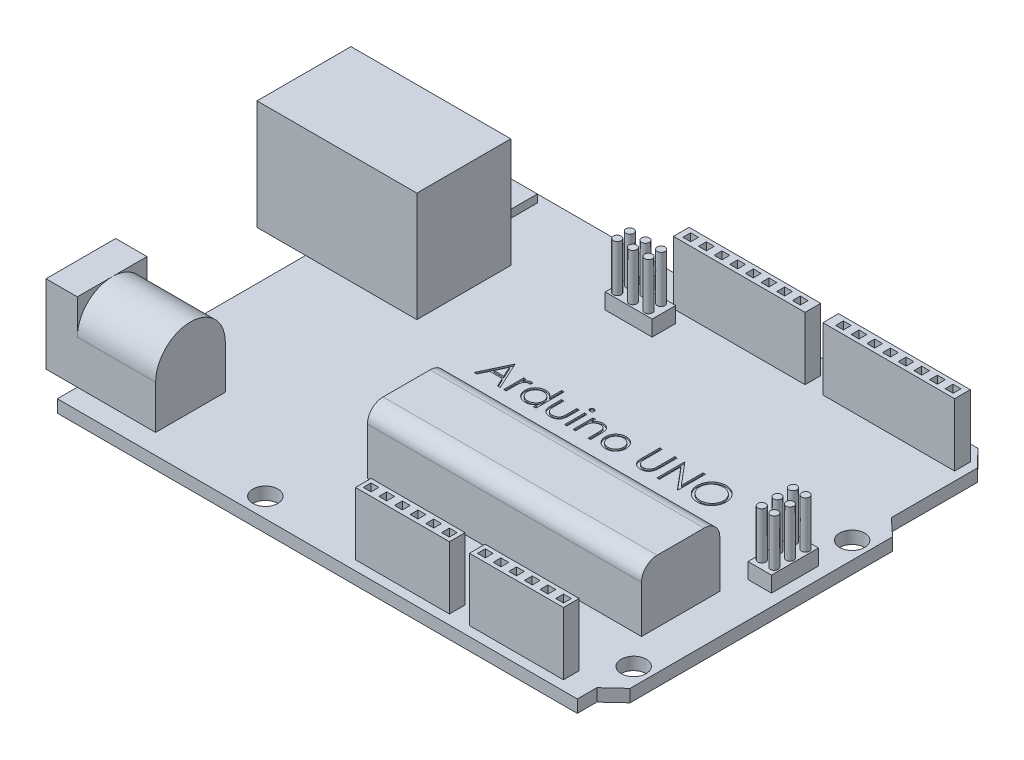
SolidWorks part; units mm, degrees
ref_plane "Plan de face" through (0, 0, 0) normal (0, 0, 1) x (1, 0, 0)
ref_plane "Plan de dessus" through (0, 0, 0) normal (0, 1, 0) x (1, 0, 0)
ref_plane "Plan de droite" through (0, 0, 0) normal (1, 0, 0) x (0, 0, -1)
sketch "Esquisse1" plane through (0, 0, 0) normal (0, 1, 0) x (1, 0, 0)
  line L0 (32.1, -43.7952) -> (32.1, 35.5676) construction
  line L1 (29.9738, 26.8233) -> (-34.3, 26.8233)
  line L2 (34.3, 11.5857) -> (34.3, -26.8233)
  line L3 (32.1, -26.4767) -> (-34.3, -26.4767)
  line L4 (-34.3, 26.8233) -> (-34.3, -26.4767)
  line L5 (34.2991, 26.4761) -> (-34.3, -26.4767) construction
  line L6 (34.3, -26.8233) -> (-34.3, 26.8233) construction
  line L7 (-10.2382, -23.9767) -> (42.0419, -23.9767) construction
  line L8 (32.1, -26.4767) -> (32.1, -23.9767)
  line L9 (32.1, -23.9767) -> (34.3, -21.9371)
  line L10 (34.3, -21.9371) -> (34.3, 11.5857)
  line L11 (34.3, 11.5857) -> (32.1, 13.6253)
  line L12 (32.1, 13.6253) -> (32.1, 24.6021)
  line L13 (32.1, 24.6021) -> (29.9738, 26.8233)
  circle A0 centre (32.1, 8.6233) radius 1.6
  circle A1 centre (32.1, -19.2767) radius 1.6
  circle A2 centre (-10.2382, -23.9767) radius 1.6
  circle A3 centre (-9.1382, 23.8233) radius 1.6
  point P0 (0, 0)
  dimension "D3" = 3.2
  dimension "D4" = 3.2
  dimension "D5" = 3.2
  dimension "D6" = 3.2
  dimension "D1" = 53.3
  dimension "D2" = 68.6
  dimension "D7" = 1.1
  dimension "D8" = 4.7
  dimension "D9" = 15.2
  dimension "D10" = 27.9
  dimension "D11" = 2.2
  dimension "D12" = 2.2
  dimension "D13" = 2.5
  dimension "D14" = 3
  dimension "D15" = 3
  dimension "D16" = 3
  dimension "D17" = 4.7
  dimension "D18" = 15.2
  dimension "D19" = 41.2382
  dimension "D20" = 42.3382
extrude "PLAQUE" add sketch "Esquisse1" along normal blind 1.6 contours L12 L13 L1 L4 L3 L8 L9 L2 L11 A3 A2 A1 A0
sketch "Esquisse3" plane through (0, 1.6, 0) normal (0, 1, 0) x (1, 0, 0)
  line L0 (-13.9042, -26.4767) -> (-13.9042, 26.8233) construction
  line L1 (32.1, -26.4767) -> (-34.3, -26.4767) construction
  line L2 (29.9738, 26.8233) -> (-34.3, 26.8233) construction
  line L4 (-34.3, 26.8233) -> (-34.3, -26.4767) construction
  line L9 (-20.0945, 17.2233) -> (-40.5, 17.2233)
  line L10 (-20.0945, 17.2233) -> (-20.0945, 5.2233)
  line L11 (-20.0945, 5.2233) -> (-40.5, 5.2233)
  line L12 (-40.5, 17.2233) -> (-40.5, 5.2233)
  line L13 (-20.0945, 17.2233) -> (-40.5, 5.2233) construction
  line L14 (-20.0945, 5.2233) -> (-40.5, 17.2233) construction
  point P10 (-30.2972, 11.2233)
  dimension "D3" = 14.2055
  dimension "D4" = 6.2
  dimension "D6" = 12
  dimension "D7" = 9.6
extrude "USB" add sketch "Esquisse3" along normal blind 14
sketch "Esquisse6" plane through (0, 1.6, 0) normal (0, 1, 0) x (1, 0, 0)
  text T0 "Arduino UNO"
extrude "Arduino UNO" cut sketch "Esquisse6" against normal blind 0.2
sketch "Esquisse7" plane through (0, 1.6, 0) normal (0, 1, 0) x (1, 0, 0)
  line L0 (-10.2382, -23.9767) -> (36.4939, -23.9767) construction
  line L1 (1.4601, -24.2464) -> (39.7542, -24.2464) construction
  line L2 (15.823, -25.4268) -> (15.823, -21.9072) construction
  line L3 (29.1021, -25.2464) -> (17.1021, -25.2464)
  line L4 (29.1021, -25.2464) -> (29.1021, -23.2464)
  line L5 (29.1021, -23.2464) -> (17.1021, -23.2464)
  line L6 (17.1021, -25.2464) -> (17.1021, -23.2464)
  line L7 (29.1021, -25.2464) -> (17.1021, -23.2464) construction
  line L8 (29.1021, -23.2464) -> (17.1021, -25.2464) construction
  line L9 (2.5439, -25.2464) -> (2.5439, -23.2464)
  line L10 (2.5439, -25.2464) -> (14.5439, -25.2464)
  line L11 (14.5439, -25.2464) -> (14.5439, -23.2464)
  line L12 (2.5439, -23.2464) -> (14.5439, -23.2464)
  line L13 (26.6165, -24.7464) -> (25.6165, -24.7464)
  line L14 (28.6165, -23.7464) -> (27.6165, -23.7464)
  line L15 (28.6165, -23.7464) -> (28.6165, -24.7464)
  line L16 (28.6165, -24.7464) -> (27.6165, -24.7464)
  line L17 (27.6165, -23.7464) -> (27.6165, -24.7464)
  line L18 (28.6165, -23.7464) -> (27.6165, -24.7464) construction
  line L19 (28.6165, -24.7464) -> (27.6165, -23.7464) construction
  line L20 (25.6165, -23.7464) -> (25.6165, -24.7464)
  line L21 (26.6165, -23.7464) -> (25.6165, -23.7464)
  line L22 (26.6165, -23.7464) -> (26.6165, -24.7464)
  line L23 (24.6165, -24.7464) -> (23.6165, -24.7464)
  line L24 (23.6165, -23.7464) -> (23.6165, -24.7464)
  line L25 (24.6165, -23.7464) -> (23.6165, -23.7464)
  line L26 (24.6165, -23.7464) -> (24.6165, -24.7464)
  line L27 (22.6165, -24.7464) -> (21.6165, -24.7464)
  line L28 (21.6165, -23.7464) -> (21.6165, -24.7464)
  line L29 (22.6165, -23.7464) -> (21.6165, -23.7464)
  line L30 (22.6165, -23.7464) -> (22.6165, -24.7464)
  line L31 (20.6165, -24.7464) -> (19.6165, -24.7464)
  line L32 (19.6165, -23.7464) -> (19.6165, -24.7464)
  line L33 (20.6165, -23.7464) -> (19.6165, -23.7464)
  line L34 (20.6165, -23.7464) -> (20.6165, -24.7464)
  line L35 (18.6165, -24.7464) -> (17.6165, -24.7464)
  line L36 (17.6165, -23.7464) -> (17.6165, -24.7464)
  line L37 (18.6165, -23.7464) -> (17.6165, -23.7464)
  line L38 (18.6165, -23.7464) -> (18.6165, -24.7464)
  line L39 (3.0294, -23.7464) -> (3.0294, -24.7464)
  line L40 (3.0294, -23.7464) -> (4.0294, -23.7464)
  line L41 (4.0294, -23.7464) -> (4.0294, -24.7464)
  line L42 (3.0294, -24.7464) -> (4.0294, -24.7464)
  line L43 (5.0294, -23.7464) -> (5.0294, -24.7464)
  line L44 (5.0294, -24.7464) -> (6.0294, -24.7464)
  line L45 (5.0294, -23.7464) -> (6.0294, -23.7464)
  line L46 (6.0294, -23.7464) -> (6.0294, -24.7464)
  line L47 (7.0294, -23.7464) -> (7.0294, -24.7464)
  line L48 (7.0294, -24.7464) -> (8.0294, -24.7464)
  line L49 (7.0294, -23.7464) -> (8.0294, -23.7464)
  line L50 (8.0294, -23.7464) -> (8.0294, -24.7464)
  line L51 (9.0294, -23.7464) -> (9.0294, -24.7464)
  line L52 (9.0294, -24.7464) -> (10.0294, -24.7464)
  line L53 (10.0294, -23.7464) -> (10.0294, -24.7464)
  line L54 (9.0294, -23.7464) -> (10.0294, -23.7464)
  line L55 (11.0294, -23.7464) -> (11.0294, -24.7464)
  line L56 (11.0294, -24.7464) -> (12.0294, -24.7464)
  line L57 (11.0294, -23.7464) -> (12.0294, -23.7464)
  line L58 (12.0294, -23.7464) -> (12.0294, -24.7464)
  line L59 (13.0294, -23.7464) -> (13.0294, -24.7464)
  line L60 (13.0294, -23.7464) -> (14.0294, -23.7464)
  line L61 (14.0294, -23.7464) -> (14.0294, -24.7464)
  line L62 (13.0294, -24.7464) -> (14.0294, -24.7464)
  line L63 (-9.1382, 23.8233) -> (35.6937, 23.8233) construction
  line L64 (13.0294, 22.8233) -> (13.0294, 24.8233) construction
  line L65 (14.171, 24.8233) -> (30.9863, 24.8233)
  line L66 (14.171, 24.8233) -> (14.171, 22.8233)
  line L67 (14.171, 22.8233) -> (30.9863, 22.8233)
  line L68 (30.9863, 24.8233) -> (30.9863, 22.8233)
  line L69 (14.171, 24.8233) -> (30.9863, 22.8233) construction
  line L70 (14.171, 22.8233) -> (30.9863, 24.8233) construction
  line L71 (-4.9275, 24.8233) -> (-4.9275, 22.8233)
  line L72 (11.8879, 22.8233) -> (-4.9275, 22.8233)
  line L73 (11.8879, 24.8233) -> (-4.9275, 24.8233)
  line L74 (11.8879, 24.8233) -> (11.8879, 22.8233)
  line L75 (28.2826, 23.3233) -> (27.2826, 23.3233)
  line L76 (30.2826, 24.3233) -> (29.2826, 24.3233)
  line L77 (30.2826, 24.3233) -> (30.2826, 23.3233)
  line L78 (30.2826, 23.3233) -> (29.2826, 23.3233)
  line L79 (29.2826, 24.3233) -> (29.2826, 23.3233)
  line L80 (30.2826, 24.3233) -> (29.2826, 23.3233) construction
  line L81 (30.2826, 23.3233) -> (29.2826, 24.3233) construction
  line L82 (27.2826, 24.3233) -> (27.2826, 23.3233)
  line L83 (28.2826, 24.3233) -> (27.2826, 24.3233)
  line L84 (28.2826, 24.3233) -> (28.2826, 23.3233)
  line L85 (26.2826, 23.3233) -> (25.2826, 23.3233)
  line L86 (25.2826, 24.3233) -> (25.2826, 23.3233)
  line L87 (26.2826, 24.3233) -> (25.2826, 24.3233)
  line L88 (26.2826, 24.3233) -> (26.2826, 23.3233)
  line L89 (24.2826, 23.3233) -> (23.2826, 23.3233)
  line L90 (23.2826, 24.3233) -> (23.2826, 23.3233)
  line L91 (24.2826, 24.3233) -> (23.2826, 24.3233)
  line L92 (24.2826, 24.3233) -> (24.2826, 23.3233)
  line L93 (22.2826, 23.3233) -> (21.2826, 23.3233)
  line L94 (21.2826, 24.3233) -> (21.2826, 23.3233)
  line L95 (22.2826, 24.3233) -> (21.2826, 24.3233)
  line L96 (22.2826, 24.3233) -> (22.2826, 23.3233)
  line L97 (20.2826, 23.3233) -> (19.2826, 23.3233)
  line L98 (19.2826, 24.3233) -> (19.2826, 23.3233)
  line L99 (20.2826, 24.3233) -> (19.2826, 24.3233)
  line L100 (20.2826, 24.3233) -> (20.2826, 23.3233)
  line L101 (18.2826, 23.3233) -> (17.2826, 23.3233)
  line L102 (17.2826, 24.3233) -> (17.2826, 23.3233)
  line L103 (18.2826, 24.3233) -> (17.2826, 24.3233)
  line L104 (18.2826, 24.3233) -> (18.2826, 23.3233)
  line L105 (16.2826, 23.3233) -> (15.2826, 23.3233)
  line L106 (15.2826, 24.3233) -> (15.2826, 23.3233)
  line L107 (16.2826, 24.3233) -> (15.2826, 24.3233)
  line L108 (16.2826, 24.3233) -> (16.2826, 23.3233)
  line L109 (-0.2237, 24.3233) -> (0.7763, 24.3233)
  line L110 (0.7763, 24.3233) -> (0.7763, 23.3233)
  line L111 (-0.2237, 23.3233) -> (0.7763, 23.3233)
  line L112 (-0.2237, 24.3233) -> (-0.2237, 23.3233)
  line L113 (-2.2237, 24.3233) -> (-2.2237, 23.3233)
  line L114 (-1.2237, 24.3233) -> (-1.2237, 23.3233)
  line L115 (-2.2237, 24.3233) -> (-1.2237, 24.3233)
  line L116 (-2.2237, 23.3233) -> (-1.2237, 23.3233)
  line L117 (-4.2237, 23.3233) -> (-3.2237, 23.3233)
  line L118 (-4.2237, 24.3233) -> (-4.2237, 23.3233)
  line L119 (-4.2237, 24.3233) -> (-3.2237, 24.3233)
  line L120 (-3.2237, 24.3233) -> (-3.2237, 23.3233)
  line L121 (1.7763, 24.3233) -> (1.7763, 23.3233)
  line L122 (2.7763, 24.3233) -> (2.7763, 23.3233)
  line L123 (1.7763, 23.3233) -> (2.7763, 23.3233)
  line L124 (1.7763, 24.3233) -> (2.7763, 24.3233)
  line L125 (3.7763, 24.3233) -> (3.7763, 23.3233)
  line L126 (3.7763, 23.3233) -> (4.7763, 23.3233)
  line L127 (3.7763, 24.3233) -> (4.7763, 24.3233)
  line L128 (4.7763, 24.3233) -> (4.7763, 23.3233)
  line L129 (5.7763, 24.3233) -> (5.7763, 23.3233)
  line L130 (6.7763, 24.3233) -> (6.7763, 23.3233)
  line L131 (5.7763, 24.3233) -> (6.7763, 24.3233)
  line L132 (5.7763, 23.3233) -> (6.7763, 23.3233)
  line L133 (7.7763, 24.3233) -> (7.7763, 23.3233)
  line L134 (8.7763, 24.3233) -> (8.7763, 23.3233)
  line L135 (7.7763, 23.3233) -> (8.7763, 23.3233)
  line L136 (7.7763, 24.3233) -> (8.7763, 24.3233)
  line L137 (9.7763, 24.3233) -> (10.7763, 24.3233)
  line L138 (10.7763, 24.3233) -> (10.7763, 23.3233)
  line L139 (9.7763, 23.3233) -> (10.7763, 23.3233)
  line L140 (9.7763, 24.3233) -> (9.7763, 23.3233)
  point P5 (23.1021, -24.2464)
  point P16 (28.1165, -24.2464)
  point P68 (22.5786, 23.8233)
  point P79 (29.7826, 23.8233)
  dimension "D1" = 2
  dimension "D2" = 12
  dimension "D3" = 1
  dimension "D4" = 1
  dimension "D6" = 2
  dimension "D7" = 1
  dimension "D8" = 1
  dimension "D5" = 6
  dimension "D9" = 8
extrude "PIN 1 " add sketch "Esquisse7" along normal blind 8
sketch "Esquisse9" plane through (-40.5, 0, 0) normal (-1, 0, 0) x (0, 0, 1)
  line L0 (-16.2233, 5.2102) -> (-16.2233, 12.2165)
  line L1 (-16.2233, 12.2165) -> (-14.2233, 14.6)
  line L2 (-14.2233, 14.6) -> (-8.2233, 14.6)
  line L3 (-8.2233, 14.6) -> (-6.2233, 12.2165)
  line L4 (-6.2233, 12.2165) -> (-6.2233, 5.2102)
  line L5 (-6.2233, 5.2102) -> (-16.2233, 5.2102)
  line L6 (-17.2233, 15.6) -> (-5.2233, 15.6) construction
  line L7 (-17.2233, 15.6) -> (-17.2233, 1.6) construction
  line L8 (-5.2233, 15.6) -> (-5.2233, 1.6) construction
  dimension "D1" = 1
  dimension "D2" = 1
  dimension "D3" = 1
  dimension "D4" = 130
  dimension "D5" = 130
  dimension "D6" = 3
  dimension "D7" = 3
extrude "USB - VIDE" cut sketch "Esquisse9" against normal blind 10
sketch "Esquisse10" plane through (0, 1.6, 0) normal (0, 1, 0) x (1, 0, 0)
  line L0 (32.1, -26.4767) -> (-34.3, -26.4767) construction
  line L1 (-34.3, 5.2233) -> (-34.3, -26.4767) construction
  line L2 (-24.3, -15.0267) -> (-38.3, -15.0267)
  line L3 (-24.3, -15.0267) -> (-24.3, -23.9267)
  line L4 (-24.3, -23.9267) -> (-38.3, -23.9267)
  line L5 (-38.3, -15.0267) -> (-38.3, -23.9267)
  line L6 (-24.3, -15.0267) -> (-38.3, -23.9267) construction
  line L7 (-24.3, -23.9267) -> (-38.3, -15.0267) construction
  point P0 (-31.3, -19.4767)
  point P3 (-31.3, -19.4767)
  dimension "D1" = 7
  dimension "D2" = 8.9
  dimension "D3" = 14
  dimension "D4" = 10
extrude "VOLT BASE" add sketch "Esquisse10" along normal blind 10
sketch "Esquisse11" plane through (-24.3, 0, 0) normal (1, 0, 0) x (0, 0, -1)
  line L0 (-23.9267, 11.6) -> (-15.0267, 1.6) construction
  line L1 (-19.4767, 6.6) -> (-19.4767, 15.9646) construction
  line L2 (-23.9267, 11.6) -> (-15.0267, 11.6) construction
  line L3 (-15.0267, 11.6) -> (-15.0267, 1.6) construction
  line L4 (-15.0267, 11.6) -> (-23.9267, 11.6)
  line L5 (-23.9267, 11.6) -> (-23.9267, 7.15)
  line L6 (-15.0267, 11.6) -> (-15.0267, 7.15)
  arc A0 (-15.0267, 7.15) -> (-23.9267, 7.15) centre (-19.4767, 7.15) ccw
  point P16 (-19.4767, 11.6)
  line M2 (-15.0267, 1.6) -> (-15.0267, 11.6)
  line M3 (-15.0267, 11.6) -> (-23.9267, 11.6)
  line M4 (-23.9267, 11.6) -> (-23.9267, 1.6)
extrude "VOLT - VIDE 1" cut sketch "Esquisse11" against normal blind 10 contours A0 L4 M4 | A0 M2 M3
sketch "Esquisse12" plane through (-38.3, 0, 0) normal (-1, 0, 0) x (0, 0, 1)
  line L0 (15.0267, 11.6) -> (23.9267, 1.6) construction
  line L1 (19.4767, 6.6) -> (19.4767, 17.3609) construction
  line L3 (15.0267, 11.6) -> (23.9267, 11.6) construction
  line L4 (19.4767, 7.15) -> (11.5595, 7.15) construction
  line L5 (11.5595, 7.15) -> (22.2871, 7.15) construction
  line L6 (15.0267, 11.6) -> (15.0267, 1.6) construction
  circle A0 centre (19.4767, 7.15) radius 3.45
  point P10 (19.4767, 10.6)
  point P11 (16.0267, 7.15)
  point P14 (22.9267, 7.15)
  dimension "D1" = 1
  dimension "D2" = 1
extrude "VOLT - VIDE 2" cut sketch "Esquisse12" against normal blind 10
sketch "Esquisse13" plane through (0, 1.6, 0) normal (0, 1, 0) x (1, 0, 0)
  line L0 (-4.5237, -10.4767) -> (28.1237, -10.4767) construction
  line L1 (32.1, -26.4767) -> (-34.3, -26.4767) construction
  line L2 (34.3, 11.5857) -> (34.3, -21.9371) construction
  line L3 (-5.7, -5.4767) -> (29.3, -5.4767)
  line L4 (-5.7, -5.4767) -> (-5.7, -15.4767)
  line L5 (-5.7, -15.4767) -> (29.3, -15.4767)
  line L6 (29.3, -5.4767) -> (29.3, -15.4767)
  line L7 (-5.7, -5.4767) -> (29.3, -15.4767) construction
  line L8 (-5.7, -15.4767) -> (29.3, -5.4767) construction
  point P4 (11.8, -10.4767)
  dimension "D1" = 16
  dimension "D2" = 10
  dimension "D3" = 35
  dimension "D4" = 5
extrude "MICROCONTROLLEUR" add sketch "Esquisse13" along normal blind 8
fillet "MICROCONTROLLEUR CONGE" radius 2 2 edges at (11.8, 9.6, 5.4767) (11.8, 9.6, 15.4767)
sketch "Esquisse14" plane through (0, 1.6, 0) normal (0, 1, 0) x (1, 0, 0)
  line L0 (34.3, 11.5857) -> (34.3, -21.9371) construction
  line L1 (32.1, 10.2233) -> (32.1, 7.0233) construction
  line L2 (29.9738, 26.8233) -> (-34.3, 26.8233) construction
  line L3 (-10.7382, 23.8233) -> (-7.5382, 23.8233) construction
  line L5 (29.8, 3.6233) -> (32.8, 3.6233)
  line L6 (29.8, 3.6233) -> (29.8, -2.3767)
  line L7 (29.8, -2.3767) -> (32.8, -2.3767)
  line L8 (32.8, 3.6233) -> (32.8, -2.3767)
  line L9 (29.8, 3.6233) -> (32.8, -2.3767) construction
  line L10 (29.8, -2.3767) -> (32.8, 3.6233) construction
  line L11 (-9.1382, 21.3233) -> (-3.1382, 21.3233)
  line L12 (-9.1382, 21.3233) -> (-9.1382, 18.3233)
  line L13 (-9.1382, 18.3233) -> (-3.1382, 18.3233)
  line L14 (-3.1382, 21.3233) -> (-3.1382, 18.3233)
  line L15 (-9.1382, 21.3233) -> (-3.1382, 18.3233) construction
  line L16 (-9.1382, 18.3233) -> (-3.1382, 21.3233) construction
  circle A0 centre (32.1, 8.6233) radius 1.6 construction
  circle A1 centre (-9.1382, 23.8233) radius 1.6 construction
  point P0 (31.3, 0.6233)
  point P1 (-6.1382, 19.8233)
  point P9 (32.1, 8.6233)
  point P17 (-9.1382, 23.8233)
  point P18 (31.3, 0.6233)
  point P23 (-6.1382, 19.8233)
  dimension "D1" = 3
  dimension "D2" = 8
  dimension "D3" = 7
  dimension "D4" = 3
  dimension "D5" = 6
  dimension "D6" = 3
  dimension "D7" = 6
  dimension "D8" = 3
extrude "PIN BASE" add sketch "Esquisse14" along normal blind 2
sketch "Esquisse15" plane through (0, 3.6, 0) normal (0, 1, 0) x (1, 0, 0)
  line L0 (31.3, 3.6233) -> (31.3, -2.3767) construction
  line L1 (32.8, 3.6233) -> (29.8, 3.6233) construction
  line L2 (29.8, -2.3767) -> (32.8, -2.3767) construction
  circle A0 centre (30.5, 2.6835) radius 0.5
  circle A1 centre (32.1, 2.6835) radius 0.5
  circle A2 centre (32.1, 0.6835) radius 0.5
  circle A3 centre (32.1, -1.3165) radius 0.5
  circle A4 centre (30.5, 0.6835) radius 0.5
  circle A5 centre (30.5, -1.3165) radius 0.5
  dimension "D1" = 1
  dimension "D2" = 0.8
  dimension "D3" = 2
  dimension "D4" = 3
extrude "PIN PIC 1" add sketch "Esquisse15" along normal blind 6
sketch "Esquisse16" plane through (0, 3.6, 0) normal (0, 1, 0) x (1, 0, 0)
  line L0 (-9.1382, 19.8233) -> (-3.1382, 19.8233) construction
  line L1 (-9.1382, 21.3233) -> (-9.1382, 18.3233) construction
  line L2 (-3.1382, 18.3233) -> (-3.1382, 21.3233) construction
  circle A0 centre (-8.2952, 19.0233) radius 0.5
  circle A1 centre (-6.2952, 19.0233) radius 0.5
  circle A2 centre (-4.2952, 19.0233) radius 0.5
  circle A3 centre (-6.2952, 20.6233) radius 0.5
  circle A4 centre (-4.2952, 20.6233) radius 0.5
  circle A5 centre (-8.2952, 20.6233) radius 0.5
  dimension "D1" = 1
  dimension "D2" = 0.8
  dimension "D3" = 3
  dimension "D4" = 2
extrude "PIN PIC 2" add sketch "Esquisse16" along normal blind 6
sketch "Esquisse17" plane through (0, 1.6, 0) normal (0, 1, 0) x (1, 0, 0)
  line L0 (-34.3, 26.8233) -> (-34.3, 17.2233) construction
  line L1 (29.9738, 26.8233) -> (-34.3, 26.8233) construction
  line L3 (-25.3, 25.8233) -> (-31.3, 25.8233)
  line L4 (-25.3, 25.8233) -> (-25.3, 19.8233)
  line L5 (-25.3, 19.8233) -> (-31.3, 19.8233)
  line L6 (-31.3, 25.8233) -> (-31.3, 19.8233)
  line L7 (-25.3, 25.8233) -> (-31.3, 19.8233) construction
  line L8 (-25.3, 19.8233) -> (-31.3, 25.8233) construction
  point P0 (-28.3, 22.8233)
  point P5 (-28.3, 22.8233)
  dimension "D1" = 6
  dimension "D2" = 4
  dimension "D3" = 6
  dimension "D4" = 6
extrude "RESET BASE" add sketch "Esquisse17" along normal blind 1
sketch "Esquisse18" plane through (0, 2.6, 0) normal (0, 1, 0) x (1, 0, 0)
  line L0 (-31.3, 25.8233) -> (-25.3, 19.8233) construction
  line L1 (-25.3, 19.8233) -> (-25.3, 25.8233) construction
  circle A0 centre (-28.3, 22.8233) radius 1.5
  dimension "D1" = 3
extrude "RESET BOUTON" add sketch "Esquisse18" along normal blind 1
